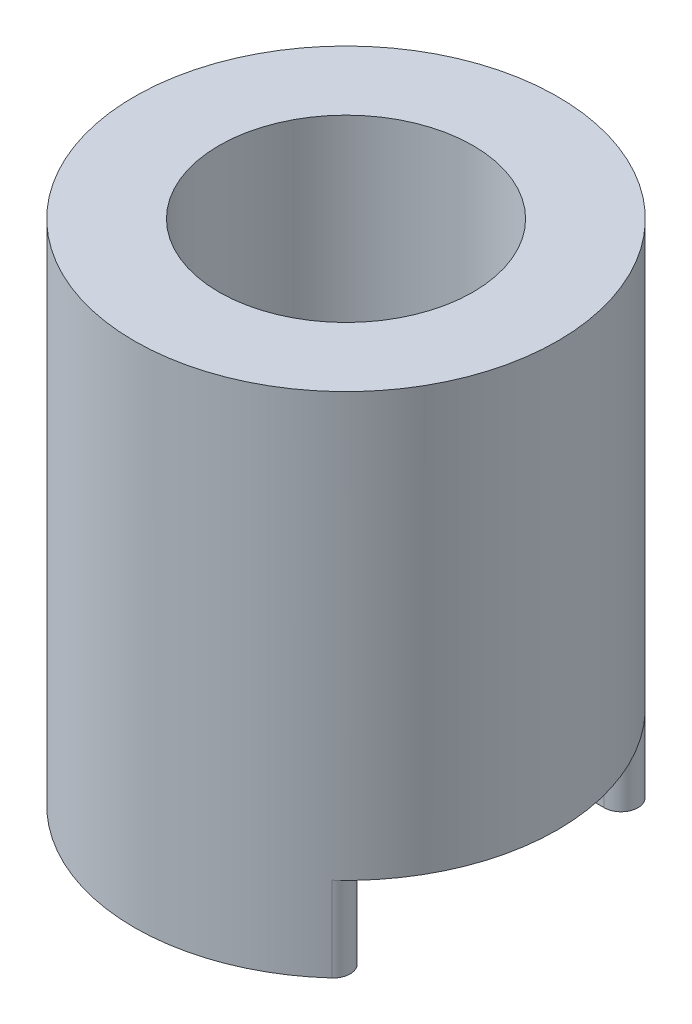
SolidWorks part; units mm, degrees
ref_plane "Front Plane" through (0, 0, 0) normal (0, 0, 1) x (1, 0, 0)
ref_plane "Top Plane" through (0, 0, 0) normal (0, 1, 0) x (1, 0, 0)
ref_plane "Right Plane" through (0, 0, 0) normal (1, 0, 0) x (0, 0, -1)
sketch "Sketch1" plane through (0, 0, 0) normal (0, 1, 0) x (1, 0, 0)
  circle A0 centre (0, 0) radius 15.875
  dimension "D1" = 31.75
extrude "Boss-Extrude1" add sketch "Sketch1" along normal blind 38.1
sketch "Sketch2" plane through (0, 0, 0) normal (1, 0, 0) x (0, 0, -1)
  line L0 (0, 0) -> (0, 50000) construction
  line L6 (-9.525, 0) -> (9.525, 0)
  line L7 (-15.875, 0) -> (15.875, 0) construction
  line L8 (9.525, 0) -> (9.525, 6.35)
  line L9 (9.525, 6.35) -> (-9.525, 6.35)
  line L10 (-9.525, 0) -> (-9.525, 6.35)
  point P0 (0, 0)
  point P11 (0, 0)
  point P12 (0, 6.35)
  dimension "D1" = 6.35
  dimension "D2" = 19.05
extrude "Cut-Extrude1" cut sketch "Sketch2" against normal through all and the other way through all
sketch "Sketch3" plane through (0, 38.1, 0) normal (0, 1, 0) x (1, 0, 0)
  circle A0 centre (0, 0) radius 9.525
  dimension "D1" = 19.05
extrude "Cut-Extrude2" cut sketch "Sketch3" against normal through all
fillet "Fillet1" radius 1.27 4 edges at (12.7, 3.175, 9.525) (-12.7, 3.175, 9.525) (12.7, 3.175, -9.525) (-12.7, 3.175, -9.525)
